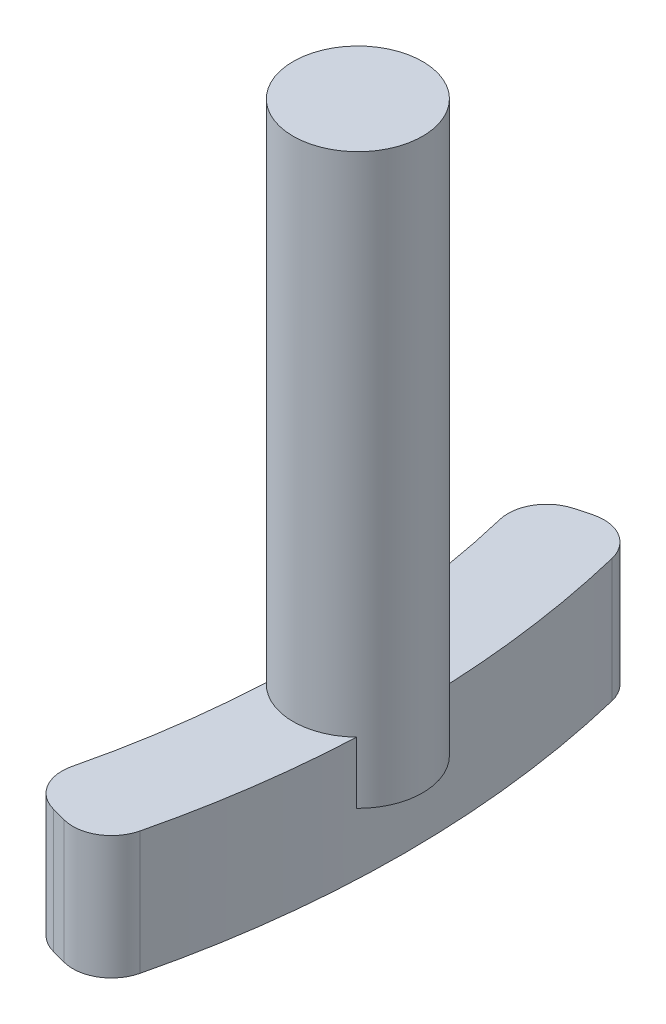
SolidWorks part; units mm, degrees
material "ABS"
ref_plane "Front Plane" through (0, 0, 0) normal (0, 0, 1) x (1, 0, 0)
ref_plane "Top Plane" through (0, 0, 0) normal (0, 1, 0) x (1, 0, 0)
ref_plane "Right Plane" through (0, 0, 0) normal (1, 0, 0) x (0, 0, -1)
sketch "Эскиз1" plane through (0, 0, 0) normal (0, 1, 0) x (1, 0, 0)
  line L4 (-1.0048, -8.4393) -> (-0.5217, -8.5687)
  line L5 (-1.0048, 8.4393) -> (-0.5217, 8.5687)
  arc A12 (-1.0048, 8.4393) -> (-1.8962, 6.9379) centre (-0.6813, 7.2319) ccw
  arc A13 (-1.8962, -6.9379) -> (-1.8962, 6.9379) centre (-30.5687, 0) ccw
  arc A14 (-1.0048, -8.4393) -> (-1.8962, -6.9379) centre (-0.6813, -7.2319) cw
  arc A15 (1.0167, -7.6558) -> (-0.5217, -8.5687) centre (-0.1981, -7.3613) cw
  arc A16 (1.0167, -7.6558) -> (1.0167, 7.6558) centre (-30.5687, 0) ccw
  arc A17 (-0.5217, 8.5687) -> (1.0167, 7.6558) centre (-0.1981, 7.3613) cw
  point P13 (0.3409, 8.2822)
  point P17 (0, 0)
  point P30 (0.3409, 8.2822)
  point P31 (0.3409, -8.2822)
extrude "Бобышка-Вытянуть1" add sketch "Эскиз1" along normal blind 4
ref_plane "Плоскость1" through (0, 2, 0) normal (0, 1, 0) x (1, 0, 0)
sketch "Эскиз2" plane through (0, 2, 0) normal (0, 1, 0) x (1, 0, 0)
  circle A2 centre (0.4313, 0) radius 2.1
  dimension "D1" = 4.2
extrude "Бобышка-Вытянуть2" add sketch "Эскиз2" along normal blind 18.44
